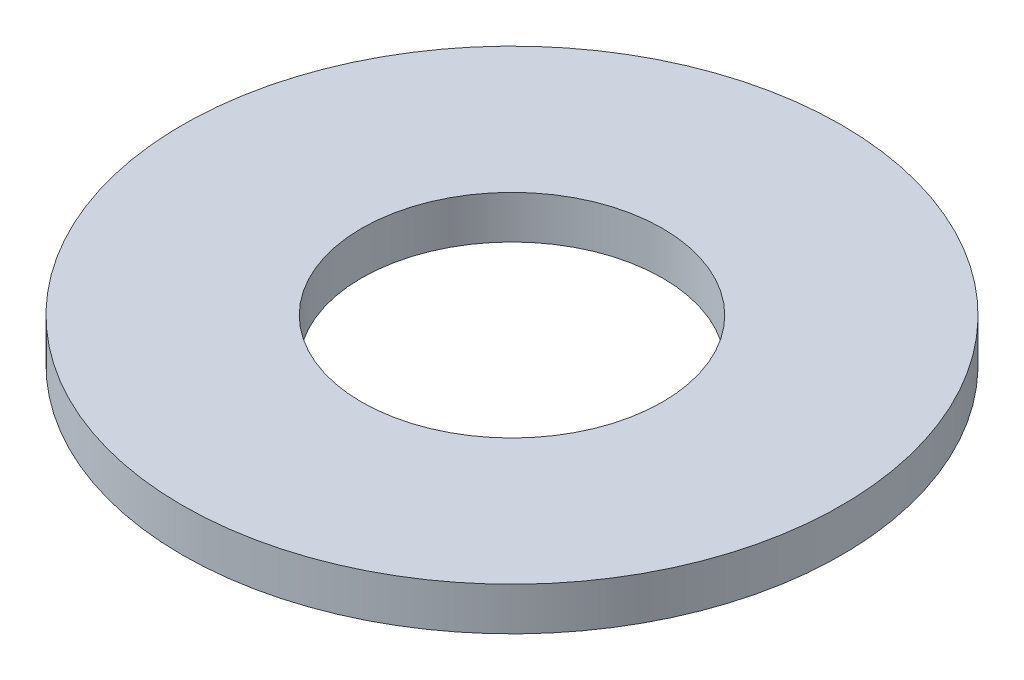
SolidWorks part; units mm, degrees
ref_plane "Front Plane" through (0, 0, 0) normal (0, 0, 1) x (1, 0, 0)
ref_plane "Top Plane" through (0, 0, 0) normal (0, 1, 0) x (1, 0, 0)
ref_plane "Right Plane" through (0, 0, 0) normal (1, 0, 0) x (0, 0, -1)
sketch "Sketch1" plane through (0, 0, 0) normal (0, 1, 0) x (1, 0, 0)
  circle A0 centre (0, 0) radius 13.335
  circle A1 centre (0, 0) radius 29.21
extrude "Boss-Extrude1" add sketch "Sketch1" along normal blind 3.81
